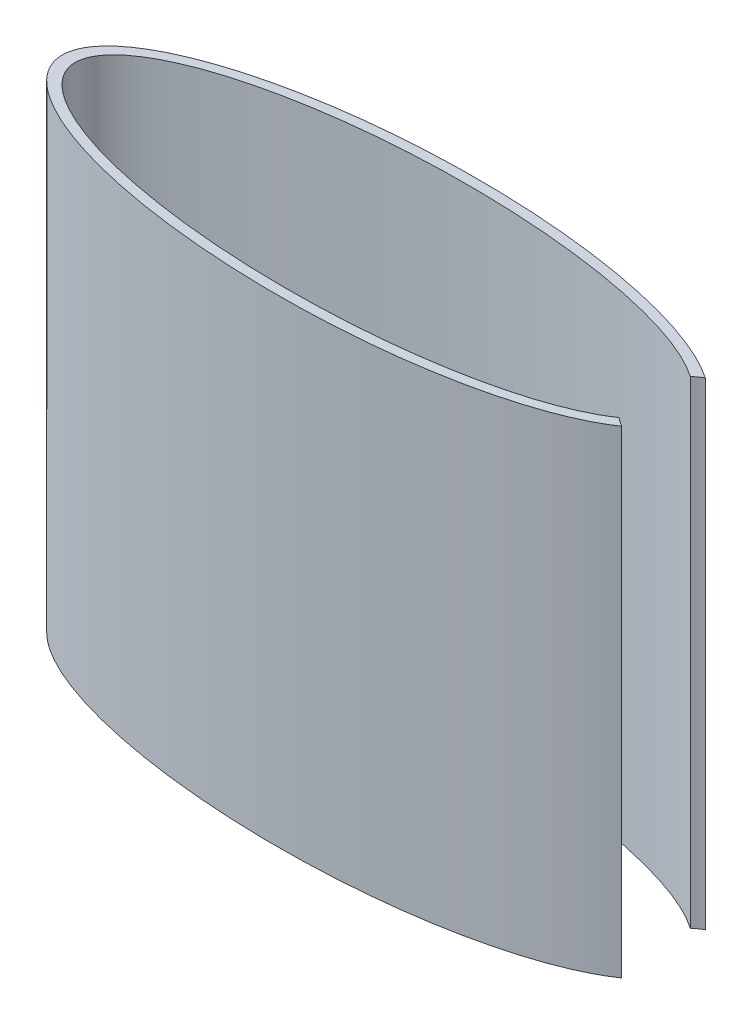
SolidWorks part; units mm, degrees
ref_plane "Front Plane" through (0, 0, 0) normal (0, 0, 1) x (1, 0, 0)
ref_plane "Top Plane" through (0, 0, 0) normal (0, 1, 0) x (1, 0, 0)
ref_plane "Right Plane" through (0, 0, 0) normal (1, 0, 0) x (0, 0, -1)
sketch "Sketch1" plane through (0, 0, 0) normal (0, 1, 0) x (1, 0, 0)
  ellipse E0 centre (0, 0) end of major axis (83.8671, 0) minor radius 26.7152
  ellipse E1 centre (0, 0) end of major axis (80.4114, 0) minor radius 24.057
extrude "Boss-Extrude1" add sketch "Sketch1" along normal blind 127.254
sketch "Sketch2" plane through (0, 127.254, 0) normal (0, 1, 0) x (1, 0, 0)
  circle A0 centre (82.3628, 0) radius 12.6959
extrude "Cut-Extrude1" cut sketch "Sketch2" against normal blind 157.48
